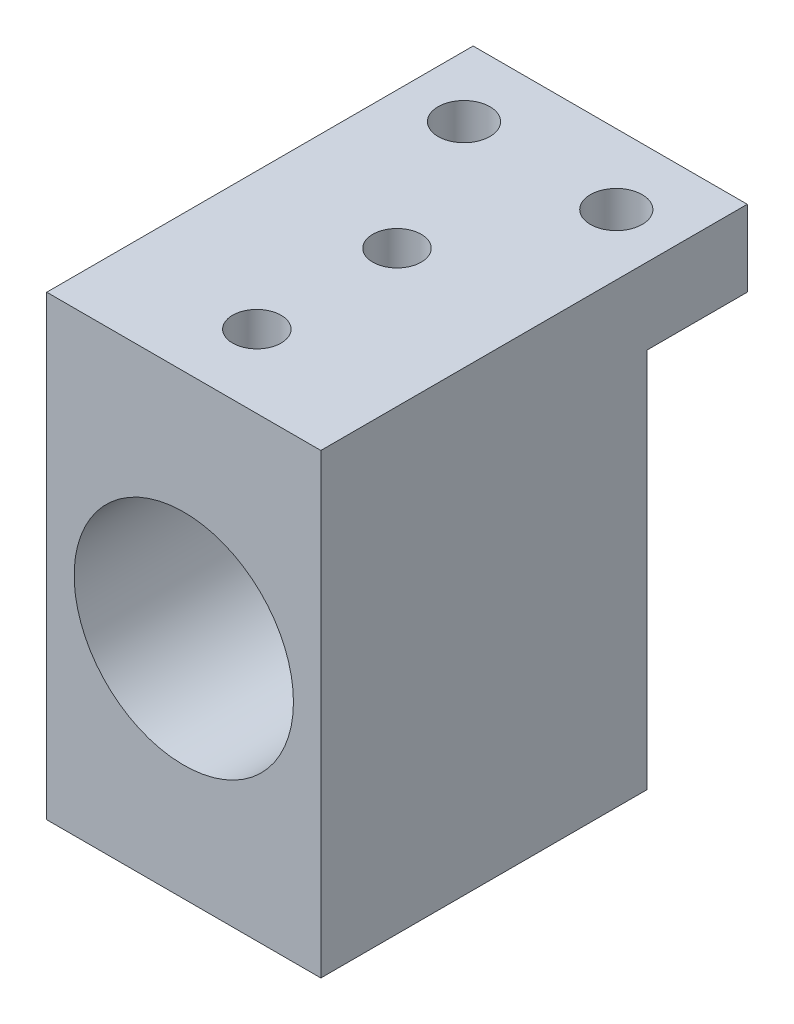
SolidWorks part; units mm, degrees
ref_plane "Front Plane" through (0, 0, 0) normal (0, 0, 1) x (1, 0, 0)
ref_plane "Top Plane" through (0, 0, 0) normal (0, 1, 0) x (1, 0, 0)
ref_plane "Right Plane" through (0, 0, 0) normal (1, 0, 0) x (0, 0, -1)
sketch "Sketch1" plane through (0, 0, 0) normal (0, 1, 0) x (1, 0, 0)
  line L1 (11.43, -17.78) -> (-11.43, -17.78)
  line L2 (11.43, -17.78) -> (11.43, 17.78)
  line L3 (11.43, 17.78) -> (-11.43, 17.78)
  line L4 (-11.43, -17.78) -> (-11.43, 17.78)
  line L5 (0, 17.78) -> (0, -17.78) construction
  line L6 (11.43, 0) -> (-11.43, 0) construction
  point P0 (0, 0)
  dimension "D1" = 22.86
  dimension "D2" = 35.56
extrude "Boss-Extrude1" add sketch "Sketch1" along normal blind 38.1
sketch "Sketch3" plane through (0, 0, 0) normal (0, -1, 0) x (1, 0, 0)
  line L0 (11.43, 17.78) -> (11.43, -17.78) construction
  line L1 (-11.43, -17.78) -> (11.43, -17.78)
  line L2 (-11.43, -17.78) -> (-11.43, -9.398)
  line L3 (-11.43, -9.398) -> (11.43, -9.398)
  line L4 (11.43, -17.78) -> (11.43, -9.398)
  line L5 (0, -9.398) -> (0, -17.78) construction
  line L6 (-11.43, -13.589) -> (11.43, -13.589) construction
  point P156 (0, -13.589)
  dimension "D1" = 8.382
extrude "Cut-Extrude2" cut sketch "Sketch3" against normal blind 31.75
sketch "Sketch4" plane through (0, 38.1, 0) normal (0, 1, 0) x (1, 0, 0)
  line L0 (0, 17.78) -> (0, -17.78) construction
  line L1 (11.43, 17.78) -> (-11.43, 17.78) construction
  line L2 (-11.43, -17.78) -> (11.43, -17.78) construction
  circle A0 centre (-6.35, 11.938) radius 2.159
  circle A2 centre (6.35, 11.938) radius 2.159
  dimension "D1" = 4.318
  dimension "D2" = 6.35
  dimension "D3" = 5.842
extrude "Cut-Extrude3" cut sketch "Sketch4" against normal blind 6.35
sketch "Sketch6" plane through (0, 0, 17.78) normal (0, 0, 1) x (1, 0, 0)
  line L0 (-11.43, 38.1) -> (11.43, 38.1) construction
  line L1 (0, -19.558) -> (0, 19.558) construction
  circle A0 centre (0, 18.796) radius 9.144
  dimension "D2" = 18.288
  dimension "D1" = 19.304
extrude "Cut-Extrude4" cut sketch "Sketch6" against normal through all
hole_wizard "#10-32 Tapped Hole1" positions "Sketch7" profile "Sketch8" tap size "#10-32" standard "ANSI Inch"
sketch "Sketch7" plane through (0, 38.1, 0) normal (0, 1, 0) x (1, 0, 0)
  point P0 (0, 0)
  point P3 (0, -11.6895)
sketch "Sketch8" plane through (0, 38.1, 0) normal (1, 0, 0) x (0, 0, 1)
  line L0 (0, 0) -> (0, 10.16)
  line L1 (0, 10.16) -> (2.0193, 10.16)
  line L2 (2.0193, 10.16) -> (2.0193, 0)
  line L5 (2.0193, 0) -> (0, 0)
  line L11 (0, -6.35) -> (0, 107.95) construction
  dimension "Thru Tap Drill Dia." = 4.0386
  dimension "Thru Tap Drill Depth" = 10.16
cosmetic thread "Hole Thread1" parameters "D2"=4.826
cosmetic thread "Hole Thread2" parameters "D2"=4.826
